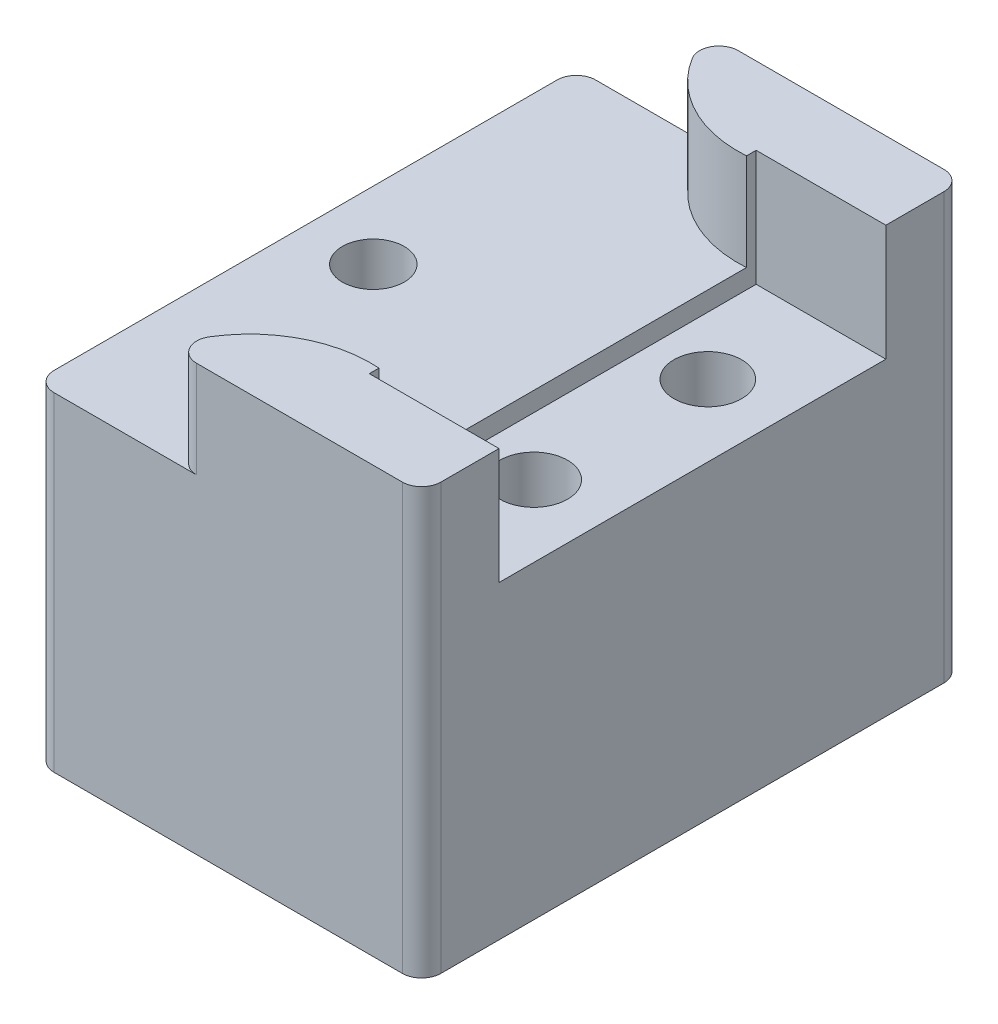
SolidWorks part; units mm, degrees
ref_plane "Alzado" through (0, 0, 0) normal (0, 0, 1) x (1, 0, 0)
ref_plane "Planta" through (0, 0, 0) normal (0, 1, 0) x (1, 0, 0)
ref_plane "Vista lateral" through (0, 0, 0) normal (1, 0, 0) x (0, 0, -1)
sketch "Croquis2" plane through (0, 0, 0) normal (0, 1, 0) x (1, 0, 0)
  line L1 (-10.8434, 8.4739) -> (9.1566, 8.4739)
  line L2 (-10.8434, 8.4739) -> (-10.8434, -19.5261)
  line L3 (-10.8434, -19.5261) -> (9.1566, -19.5261)
  line L4 (9.1566, 8.4739) -> (9.1566, -19.5261)
  dimension "D1" = 20
  dimension "D2" = 28
extrude "Saliente-Extruir1" add sketch "Croquis2" along normal blind 22
sketch "Croquis3" plane through (0, 22, 0) normal (0, 1, 0) x (1, 0, 0)
  line L0 (9.1566, 4.4739) -> (1.1799, 4.4739) construction
  line L1 (9.1566, -19.5261) -> (9.1566, 8.4739) construction
  line L2 (9.1566, -15.5261) -> (5.7192, -15.5261) construction
  line L5 (9.1566, 8.4739) -> (-10.8434, 8.4739) construction
  line L6 (9.1566, 4.4739) -> (2.4509, 4.4739)
  line L7 (9.1566, 4.4739) -> (9.1566, -15.5261)
  line L8 (9.1566, -15.5261) -> (2.4509, -15.5261)
  line L9 (2.4509, 4.4739) -> (2.4509, -15.5261)
  point P6 (0, 0)
  point P7 (0, 0)
  dimension "D1" = 20
  dimension "D2" = 4
extrude "Cortar-Extruir1" cut sketch "Croquis3" against normal blind 6
sketch "Croquis5" plane through (0, 22, 0) normal (0, 1, 0) x (1, 0, 0)
  line L0 (2.4509, 4.4739) -> (-1.2584, 4.9739) construction
  line L1 (2.4509, -15.5261) -> (0, -8.0261) construction
  line L2 (2.4509, 4.4739) -> (2.4509, -15.5261) construction
  line L3 (2.4509, 3.9739) -> (1.59, 3.9739)
  line L4 (2.4509, 3.9739) -> (2.4509, -15.0261)
  line L5 (2.4509, -15.0261) -> (1.59, -15.0261)
  line L7 (-10.8434, 8.4739) -> (9.1566, -19.5261) construction
  line L8 (-0.8434, -5.5261) -> (2.4509, -5.5261) construction
  line L9 (9.1566, 8.4739) -> (-10.8434, 8.4739) construction
  arc A0 (2.4509, 3.9739) -> (-4.0017, 8.4739) centre (2.0204, 10.2329) cw
  arc A1 (2.4509, -15.0261) -> (-4.0017, -19.5261) centre (2.0204, -21.2851) ccw
  line M7 (2.4509, -15.5261) -> (2.4509, 4.4739)
  line M10 (9.1566, 8.4739) -> (-10.8434, 8.4739)
  line M11 (-10.8434, 8.4739) -> (-10.8434, -19.5261)
  line M12 (-10.8434, -19.5261) -> (9.1566, -19.5261)
  dimension "D2" = 19
extrude "Cortar-Extruir2" cut sketch "Croquis5" against normal blind 5 contours A1 A0 M7 M10 M11 M12
sketch "Croquis6" plane through (0, 17, 0) normal (0, 1, 0) x (1, 0, 0)
  line L0 (-7.3434, 8.4739) -> (-7.3434, -19.5261) construction
  line L1 (-4.0017, 8.4739) -> (-10.8434, 8.4739) construction
  line L2 (-10.8434, -19.5261) -> (-4.0017, -19.5261) construction
  line L3 (-10.8434, 8.4739) -> (-10.8434, -19.5261) construction
  circle A0 centre (-7.3434, -5.5261) radius 1.6
  dimension "D2" = 3.2
  dimension "D1" = 3.5
extrude "Cortar-Extruir3" cut sketch "Croquis6" against normal blind 23.6784
fillet "Redondeo1" radius 1 6 edges at (-4.0017, 19.5, -8.4739) (-4.0017, 19.5, 19.5261) (9.1566, 11, -8.4739) (-10.8434, 8.5, -8.4739) (-10.8434, 8.5, 19.5261) (9.1566, 11, 19.5261)
sketch "Sketch1" plane through (0, 16, 0) normal (0, 1, 0) x (1, 0, 0)
  line L0 (9.1566, 4.4739) -> (2.4509, 4.4739) construction
  line L4 (2.4509, 4.4739) -> (2.4509, -15.5261) construction
  circle A0 centre (5.4509, -1.0261) radius 1.75
  circle A1 centre (5.4509, -10.0261) radius 1.75
  point P4 (0, 0)
  point P5 (0, 0)
  dimension "D1" = 9
  dimension "D2" = 3.5
  dimension "D3" = 3.5
  dimension "D4" = 5.5
  dimension "D5" = 3
extrude "Cut-Extrude1" cut sketch "Sketch1" against normal through all
